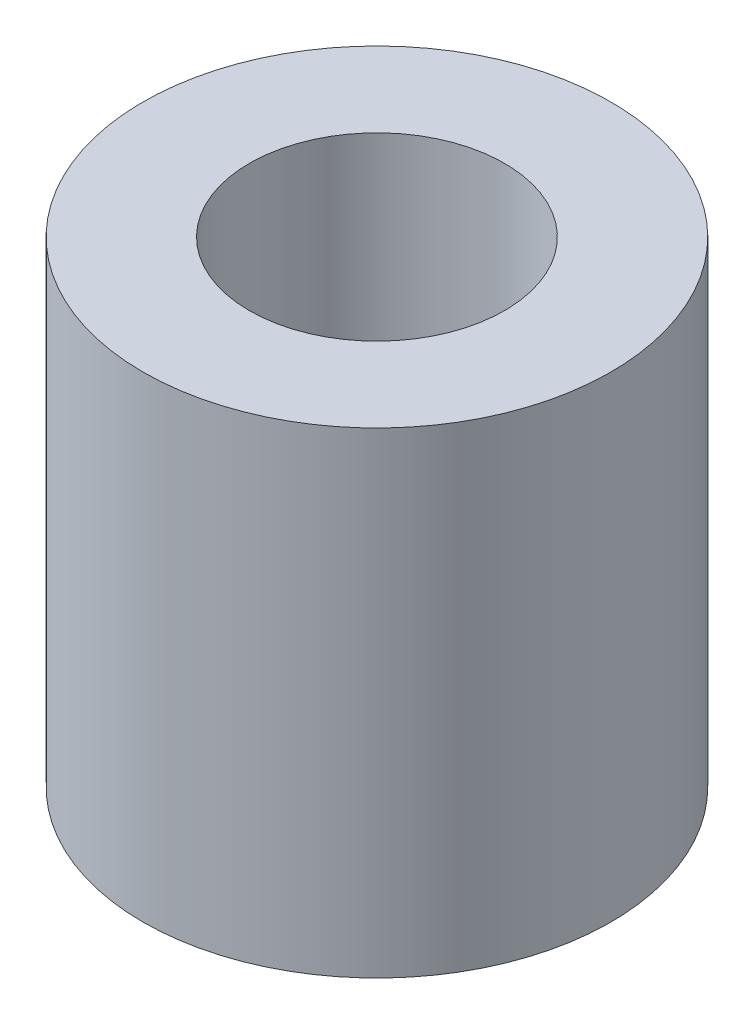
SolidWorks part; units mm, degrees
ref_plane "Front Plane" through (0, 0, 0) normal (0, 0, 1) x (1, 0, 0)
ref_plane "Top Plane" through (0, 0, 0) normal (0, 1, 0) x (1, 0, 0)
ref_plane "Right Plane" through (0, 0, 0) normal (1, 0, 0) x (0, 0, -1)
sketch "Sketch1" plane through (0, 0, 0) normal (0, 1, 0) x (1, 0, 0)
  circle A0 centre (0, 0) radius 1.5
  circle A1 centre (0, 0) radius 2.75
  dimension "D1" = 3
  dimension "D2" = 5.5
extrude "Boss-Extrude1" add sketch "Sketch1" along normal blind 5.6
